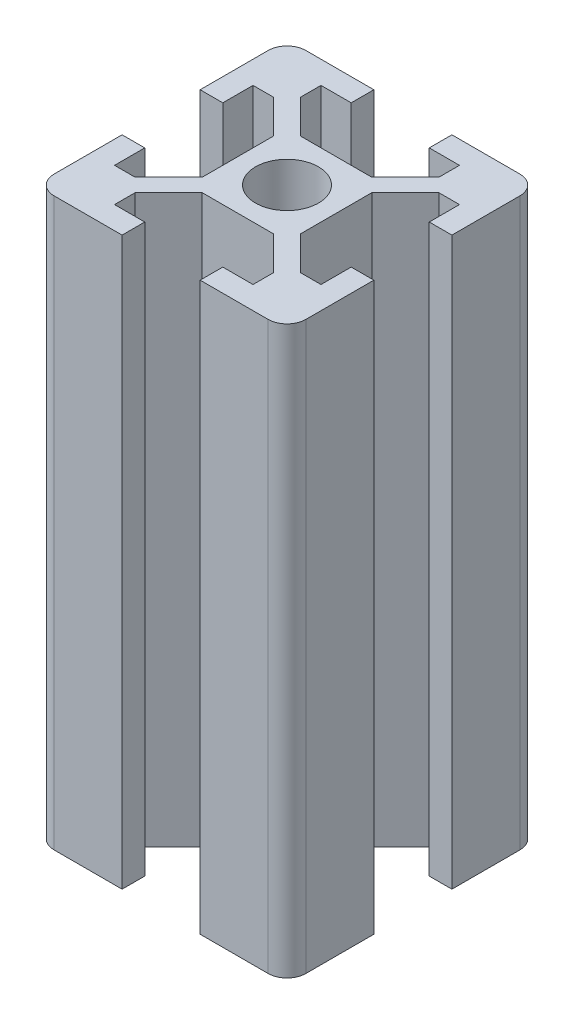
SolidWorks part; units mm, degrees
ref_plane "Płaszczyzna przednia" through (0, 0, 0) normal (0, 0, 1) x (1, 0, 0)
ref_plane "Płaszczyzna górna" through (0, 0, 0) normal (0, 1, 0) x (1, 0, 0)
ref_plane "Płaszczyzna prawa" through (0, 0, 0) normal (1, 0, 0) x (0, 0, -1)
sketch "Szkic1" plane through (0, 0, 0) normal (0, 1, 0) x (1, 0, 0)
  line L0 (0, 10) -> (0, -10) construction
  line L1 (-10, 0) -> (10, 0) construction
  line L2 (0, 3.9) -> (2.8393, 3.9)
  line L3 (3.9, 2.8393) -> (3.9, 0)
  line L4 (10, 3.1) -> (10, 8.5)
  line L5 (8.5, 10) -> (3.1, 10)
  line L6 (3.1, 10) -> (3.1, 8.2)
  line L7 (3.1, 8.2) -> (5.5, 8.2)
  line L8 (5.5, 8.2) -> (5.5, 6.5607)
  line L9 (5.5, 6.5607) -> (2.8393, 3.9)
  line L10 (3.9, 2.8393) -> (6.5607, 5.5)
  line L11 (6.5607, 5.5) -> (8.2, 5.5)
  line L12 (8.2, 5.5) -> (8.2, 3.1)
  line L13 (8.2, 3.1) -> (10, 3.1)
  line L14 (3.9, 0) -> (3.9, -2.8393)
  line L15 (2.8393, -3.9) -> (0, -3.9)
  line L16 (3.1, -10) -> (8.5, -10)
  line L17 (10, -8.5) -> (10, -3.1)
  line L18 (10, -3.1) -> (8.2, -3.1)
  line L19 (8.2, -3.1) -> (8.2, -5.5)
  line L20 (8.2, -5.5) -> (6.5607, -5.5)
  line L21 (6.5607, -5.5) -> (3.9, -2.8393)
  line L22 (2.8393, -3.9) -> (5.5, -6.5607)
  line L23 (5.5, -6.5607) -> (5.5, -8.2)
  line L24 (5.5, -8.2) -> (3.1, -8.2)
  line L25 (3.1, -8.2) -> (3.1, -10)
  line L26 (10, 0) -> (-10, 0) construction
  line L27 (0, 10) -> (0, -10) construction
  line L28 (0, -3.9) -> (-2.8393, -3.9)
  line L29 (-3.9, -2.8393) -> (-3.9, 0)
  line L30 (-10, -3.1) -> (-10, -8.5)
  line L31 (-8.5, -10) -> (-3.1, -10)
  line L32 (-3.1, -10) -> (-3.1, -8.2)
  line L33 (-3.1, -8.2) -> (-5.5, -8.2)
  line L34 (-5.5, -8.2) -> (-5.5, -6.5607)
  line L35 (-5.5, -6.5607) -> (-2.8393, -3.9)
  line L36 (-3.9, -2.8393) -> (-6.5607, -5.5)
  line L37 (-6.5607, -5.5) -> (-8.2, -5.5)
  line L38 (-8.2, -5.5) -> (-8.2, -3.1)
  line L39 (-8.2, -3.1) -> (-10, -3.1)
  line L40 (0, -10) -> (0, 10) construction
  line L41 (10, 0) -> (-10, 0) construction
  line L42 (-3.9, 0) -> (-3.9, 2.8393)
  line L43 (-2.8393, 3.9) -> (0, 3.9)
  line L44 (-3.1, 10) -> (-8.5, 10)
  line L45 (-10, 8.5) -> (-10, 3.1)
  line L46 (-10, 3.1) -> (-8.2, 3.1)
  line L47 (-8.2, 3.1) -> (-8.2, 5.5)
  line L48 (-8.2, 5.5) -> (-6.5607, 5.5)
  line L49 (-6.5607, 5.5) -> (-3.9, 2.8393)
  line L50 (-2.8393, 3.9) -> (-5.5, 6.5607)
  line L51 (-5.5, 6.5607) -> (-5.5, 8.2)
  line L52 (-5.5, 8.2) -> (-3.1, 8.2)
  line L53 (-3.1, 8.2) -> (-3.1, 10)
  line L54 (-10, 0) -> (10, 0) construction
  line L55 (0, -10) -> (0, 10) construction
  arc A0 (2.5, 0) -> (0, 2.5) centre (0, 0) ccw
  arc A1 (10, 8.5) -> (8.5, 10) centre (8.5, 8.5) ccw
  arc A2 (0, -2.5) -> (2.5, 0) centre (0, 0) ccw
  arc A3 (8.5, -10) -> (10, -8.5) centre (8.5, -8.5) ccw
  arc A4 (-2.5, 0) -> (0, -2.5) centre (0, 0) ccw
  arc A5 (-10, -8.5) -> (-8.5, -10) centre (-8.5, -8.5) ccw
  arc A6 (0, 2.5) -> (-2.5, 0) centre (0, 0) ccw
  arc A7 (-8.5, 10) -> (-10, 8.5) centre (-8.5, 8.5) ccw
  point P6 (0, 0)
  point P90 (0, 0)
  dimension "D2" = 45
  dimension "D3" = 2.5
  dimension "D7" = 1.5
  dimension "D1" = 20
  dimension "D4" = 6.1
  dimension "D5" = 11
  dimension "D6" = 6.2
  dimension "D8" = 1.8
  dimension "D9" = 1.5
  dimension "D10" = 4
extrude "Dodanie-wyciągnięcie1" add sketch "Szkic1" along normal blind 45 contours L44 A7 L45 L46 L47 L48 L49 L42 L29 L36 L37 L38 L39 L30 A5 L31 L32 L33 L34 L35 L28 L15 L22 L23 L24 L25 L16 A3 L17 L18 L19 L20 L21 L14 L3 L10 L11 L12 L13 L4 A1 L5 L6 L7 L8 L9 L2 L43 L50 L51 L52
